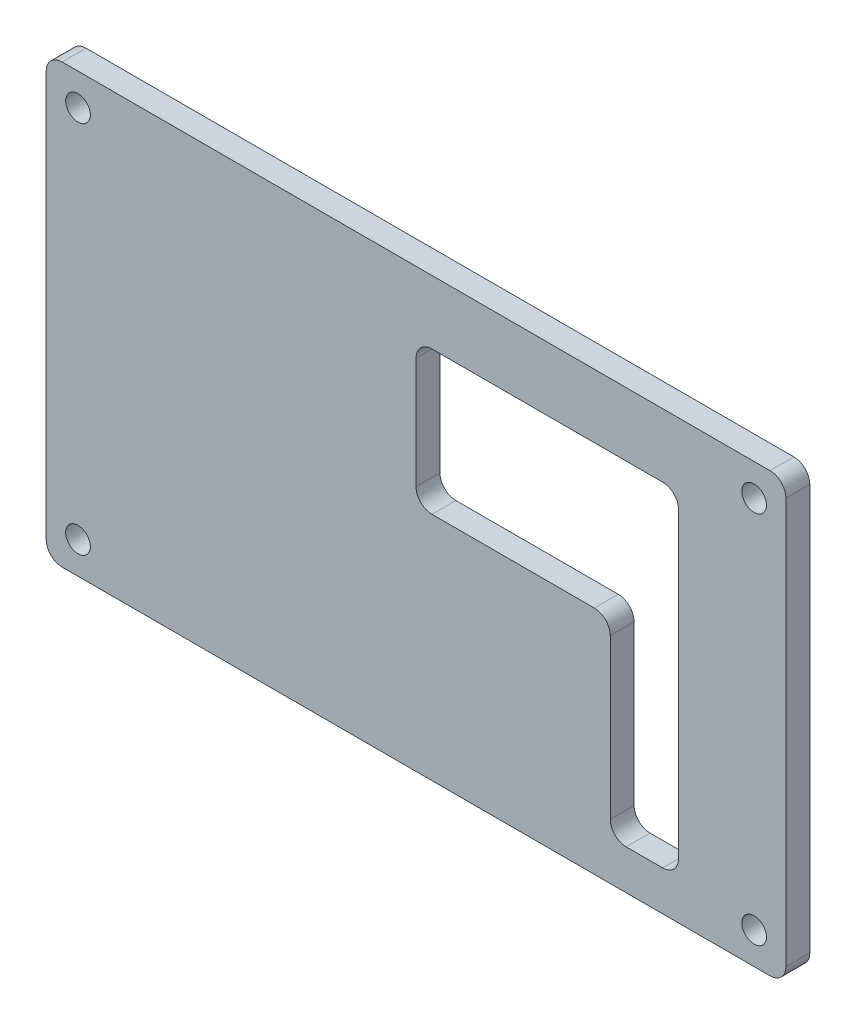
SolidWorks part; units mm, degrees
ref_plane "Plan de face" through (0, 0, 0) normal (0, 0, 1) x (1, 0, 0)
ref_plane "Plan de dessus" through (0, 0, 0) normal (0, 1, 0) x (1, 0, 0)
ref_plane "Plan de droite" through (0, 0, 0) normal (1, 0, 0) x (0, 0, -1)
sketch "Esquisse1" plane through (0, 0, 0) normal (0, 0, 1) x (1, 0, 0)
  line L0 (-46.5, 25.5) -> (-46.5, -25.5)
  line L2 (44.5, 27.5) -> (-44.5, 27.5)
  line L4 (46.5, -25.5) -> (46.5, 25.5)
  line L5 (-44.5, -27.5) -> (44.5, -27.5)
  line L6 (31, 19.5) -> (2, 19.5)
  line L7 (0, 17.5) -> (0, 3.5)
  line L8 (2, 1.5) -> (22.4132, 1.5)
  line L9 (33, -20.5) -> (33, 17.5)
  line L10 (26.4132, -22.5) -> (31, -22.5)
  line L11 (24.4132, -0.5) -> (24.4132, -20.5)
  arc A0 (46.5, 25.5) -> (44.5, 27.5) centre (44.5, 25.5) ccw
  arc A1 (44.5, -27.5) -> (46.5, -25.5) centre (44.5, -25.5) ccw
  arc A2 (-46.5, -25.5) -> (-44.5, -27.5) centre (-44.5, -25.5) ccw
  arc A3 (-44.5, 27.5) -> (-46.5, 25.5) centre (-44.5, 25.5) ccw
  circle A4 centre (-42.5, 23.5) radius 1.55
  circle A5 centre (-42.5, -23.5) radius 1.55
  circle A6 centre (42.5, 23.5) radius 1.55
  circle A7 centre (42.5, -23.5) radius 1.55
  arc A8 (2, 19.5) -> (0, 17.5) centre (2, 17.5) ccw
  arc A9 (33, 17.5) -> (31, 19.5) centre (31, 17.5) ccw
  arc A10 (31, -22.5) -> (33, -20.5) centre (31, -20.5) ccw
  arc A11 (24.4132, -20.5) -> (26.4132, -22.5) centre (26.4132, -20.5) ccw
  arc A12 (24.4132, -0.5) -> (22.4132, 1.5) centre (22.4132, -0.5) ccw
  arc A13 (0, 3.5) -> (2, 1.5) centre (2, 3.5) ccw
  dimension "D1" = 3.1
  dimension "D2" = 2
  dimension "D3" = 93
  dimension "D4" = 55
  dimension "D5" = 8
  dimension "D6" = 18
  dimension "D7" = 24
  dimension "D8" = 13.5
  dimension "D9" = 33
  dimension "D10" = 24.4132
  dimension "D11" = 27.5
  dimension "D12" = 46.5
  dimension "D13" = 4
  dimension "D14" = 4
  dimension "D15" = 4
  dimension "D16" = 4
extrude "Boss.-Extru.1" add sketch "Esquisse1" along normal blind 3
